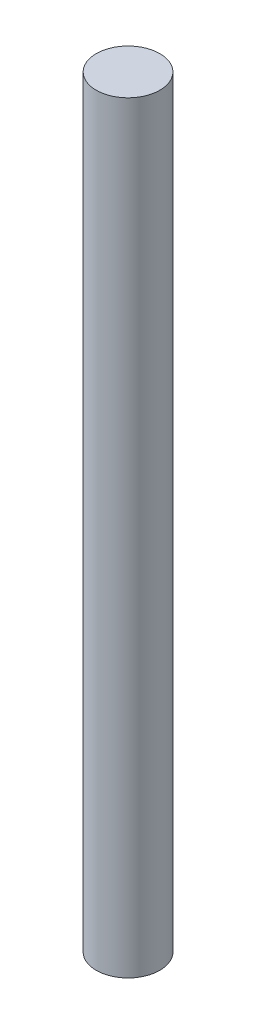
SolidWorks part; units mm, degrees
ref_plane "Front Plane" through (0, 0, 0) normal (0, 0, 1) x (1, 0, 0)
ref_plane "Top Plane" through (0, 0, 0) normal (0, 1, 0) x (1, 0, 0)
ref_plane "Right Plane" through (0, 0, 0) normal (1, 0, 0) x (0, 0, -1)
sketch "Sketch1" plane through (0, 0, 0) normal (0, 1, 0) x (1, 0, 0)
  circle A0 centre (0, 0) radius 6.35
extrude "Boss-Extrude1" add sketch "Sketch1" along normal blind 152.4
